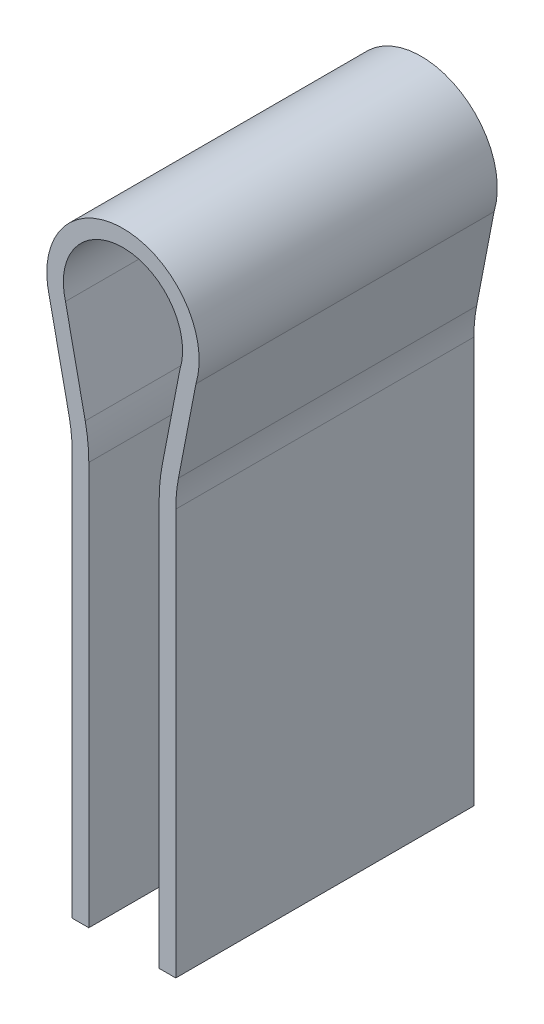
SolidWorks part; units mm, degrees
material "Stal węglowa"
ref_plane "Płaszczyzna przednia" through (0, 0, 0) normal (0, 0, 1) x (1, 0, 0)
ref_plane "Płaszczyzna górna" through (0, 0, 0) normal (0, 1, 0) x (1, 0, 0)
ref_plane "Płaszczyzna prawa" through (0, 0, 0) normal (1, 0, 0) x (0, 0, -1)
sketch "Szkic2" plane through (0, 0, 0) normal (0, 0, 1) x (1, 0, 0)
  line L0 (0, 0) -> (0, 24.3302)
  line L1 (4.25, 0) -> (4.25, 24.5112)
  line L2 (-0.2156, 26.3954) -> (-1.4073, 32.0414)
  line L3 (4.4316, 26.4082) -> (5.4958, 31.9164)
  line L4 (-1, 0) -> (-1, 24.3302)
  line L5 (-1.194, 26.1889) -> (-2.3798, 31.8067)
  line L6 (5.4134, 26.2185) -> (6.4674, 31.6737)
  line L7 (5.25, 0) -> (5.25, 24.5112)
  line L8 (-1, 0) -> (0, 0)
  line L9 (4.25, 0) -> (5.25, 0)
  arc A1 (5.4958, 31.9164) -> (-1.4073, 32.0414) centre (2.0628, 32.9999) ccw
  arc A2 (0, 24.3302) -> (-0.2156, 26.3954) centre (-10, 24.3302) ccw
  arc A3 (4.25, 24.5112) -> (4.4316, 26.4082) centre (14.25, 24.5112) cw
  arc A4 (-1, 24.3302) -> (-1.194, 26.1889) centre (-10, 24.3302) ccw
  arc A5 (6.4674, 31.6737) -> (-2.3798, 31.8067) centre (2.0628, 32.9999) ccw
  arc A6 (5.25, 24.5112) -> (5.4134, 26.2185) centre (14.25, 24.5112) cw
  point P13 (0, 25.3741)
  dimension "D5" = 5.6178
  dimension "D3" = 10
  dimension "D4" = 10
  dimension "D6" = 3.6
  dimension "D8" = 4.6
  dimension "D2" = 4.25
  dimension "D7" = 32.9999
  dimension "D9" = 5.4552
  dimension "D10" = 26.3954
  dimension "D12" = 1
  dimension "D13" = 4.25
  dimension "D14" = 32.0414
  dimension "D15" = 6.9031
  dimension "D11" = 1
extrude "Dodanie-wyciągnięcie1" add sketch "Szkic2" along normal blind 18 contours L1 A3 L3 A1 L2 A2 L0 L8 L4 A4 L5 A5 L6 A6 L7 L9
